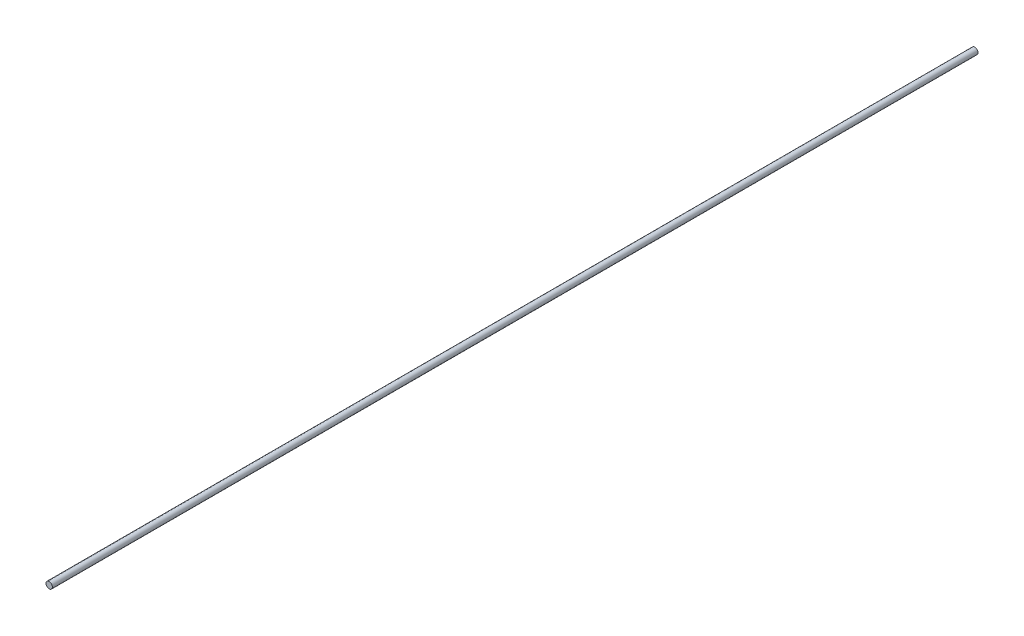
SolidWorks part; units mm, degrees
material "1023 碳钢板 (SS)"
ref_plane "Front" through (0, 0, 0) normal (0, 0, 1) x (1, 0, 0)
ref_plane "Top" through (0, 0, 0) normal (0, 1, 0) x (1, 0, 0)
ref_plane "Right" through (0, 0, 0) normal (1, 0, 0) x (0, 0, -1)
sketch "草图1" plane through (0, 0, 0) normal (0, 0, 1) x (1, 0, 0)
  circle A0 centre (0, 0) radius 1
  dimension "D1" = 2
extrude "凸台-拉伸1" add sketch "草图1" along normal blind 290
